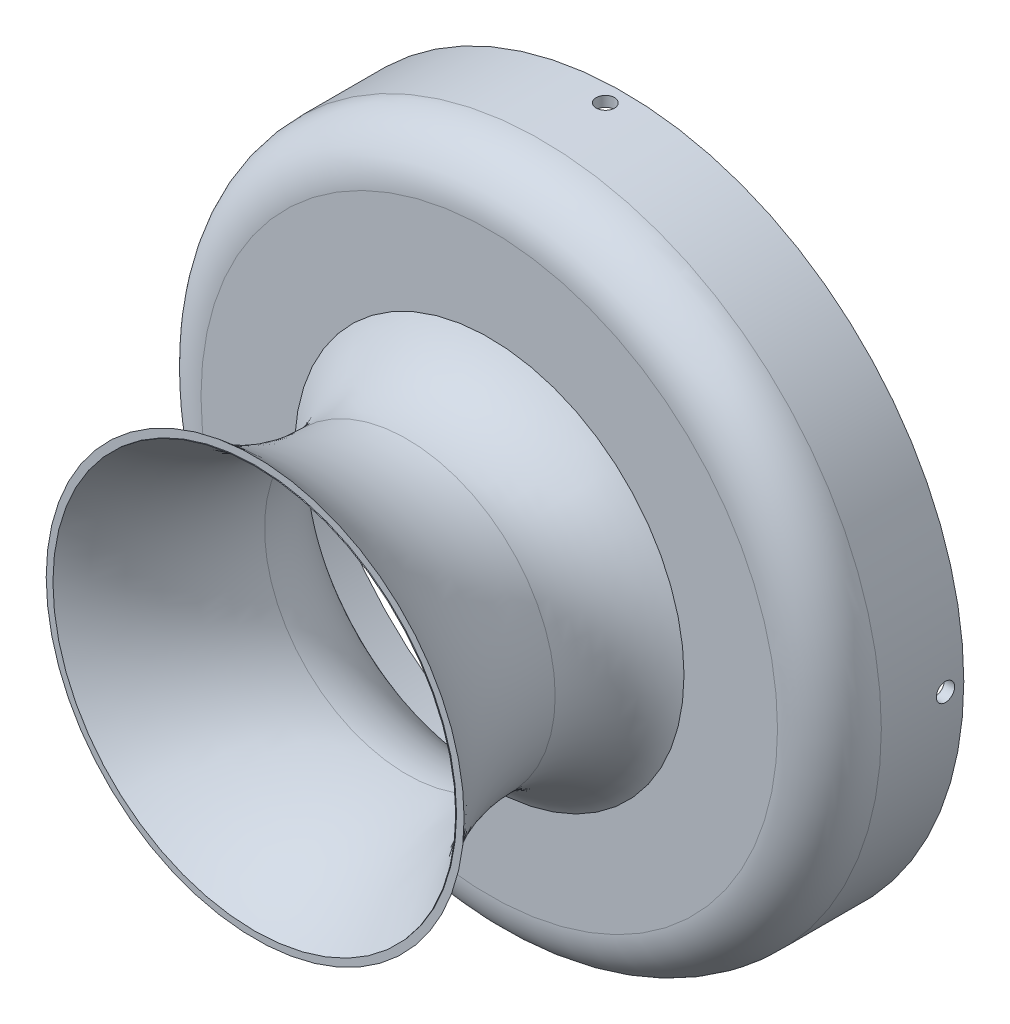
SolidWorks part; units mm, degrees
material "7079 Alloy"
ref_plane "Front Plane" through (0, 0, 0) normal (0, 0, 1) x (1, 0, 0)
ref_plane "Top Plane" through (0, 0, 0) normal (0, 1, 0) x (1, 0, 0)
ref_plane "Right Plane" through (0, 0, 0) normal (1, 0, 0) x (0, 0, -1)
sketch "Sketch1" plane through (0, 0, 0) normal (0, 1, 0) x (1, 0, 0)
  line L0 (-33.62, 40.5) -> (-47.2, 40.5)
  line L1 (-53.7, 47) -> (-53.7, 47.5)
  line L3 (-55.7, 60.5) -> (-55.7, 47)
  line L4 (-24.3, 25) -> (-23.3, 25)
  line L5 (-47.2, 38.5) -> (-31.8909, 38.5)
  line L6 (0, 0) -> (0, 26.6863) construction
  line L7 (-54, 49.5) -> (-54, 47.7)
  line L8 (-54, 47.7) -> (-53.7, 47.7)
  line L10 (-55.7, 60.5) -> (-54, 60.5)
  line L11 (-54, 49.5) -> (-54, 60.5)
  line L12 (-53.7, 47.7) -> (-53.7, 47.5)
  arc A0 (-23.3, 25) -> (-33.62, 40.5) centre (-40.1, 25) ccw
  arc A1 (-24.3, 25) -> (-31.8909, 38.5) centre (-40.1, 25) ccw
  arc A2 (-53.7, 47) -> (-47.2, 40.5) centre (-47.2, 47) ccw
  arc A3 (-47.2, 38.5) -> (-55.7, 47) centre (-47.2, 47) cw
  point P0 (-53.7, 40.5)
  point P15 (-53.7, 40.5)
  dimension "D1" = 6.5
  dimension "D2" = 8.5
revolve "Revolve1" add sketch "Sketch1" angle 360 about L6
ref_plane "Plane1" through (0, 55.7, 0) normal (0, 1, 0) x (1, 0, 0)
sketch "Sketch2" plane through (0, 55.7, 0) normal (0, 1, 0) x (1, 0, 0)
  circle A0 centre (0, 57.5) radius 1.5
  point P6 (0, 57.5)
extrude "Cut-Extrude1" cut sketch "Sketch2" against normal blind 10
pattern_circular "CirPattern1" count 4 over 360 about axis through (0, 0, 0) along (0, 0, 1) of "Cut-Extrude1"
sketch "Sketch4" plane through (0, 0, 0) normal (0, 1, 0) x (1, 0, 0)
  line L1 (-23.3, 25) -> (23.3, 25) construction
  line L2 (-24.3, 25) -> (24.3, 25) construction
  line L3 (-24.3, 25) -> (-23.3, 25)
  line L4 (-33.0079, 0) -> (-34.3791, 0)
  line L5 (0, 0) -> (0, 19.2361) construction
  arc A0 (-24.3, 25) -> (-34.3791, 0) centre (-60.3442, 25) cw
  arc A1 (-23.3, 25) -> (-33.0079, 0) centre (-60.3442, 25) cw
  point P0 (-23.3, 25)
  point P2 (-24.3, 25)
revolve "Revolve2" add sketch "Sketch4" angle 360 about L5
sketch "Sketch12" plane through (0, 0, 0) normal (1, 0, 0) x (0, 0, -1)
  line L0 (0.172, 34.8048) -> (0.172, 32.9773)
  line L1 (0.172, 32.9773) -> (-3.2949, 32.9773)
  line L2 (-3.2949, 32.9773) -> (0.172, 34.8048)
  line L3 (-33.8409, 0) -> (0, 0) construction
revolve "Cut-Revolve2" cut sketch "Sketch12" angle 360 about L3
